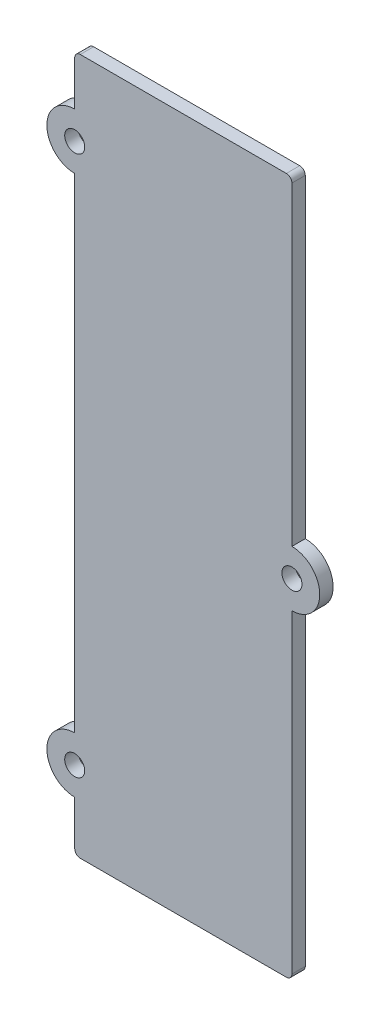
SolidWorks part; units mm, degrees
material "PET"
ref_plane "Front Plane" through (0, 0, 0) normal (0, 0, 1) x (1, 0, 0)
ref_plane "Top Plane" through (0, 0, 0) normal (0, 1, 0) x (1, 0, 0)
ref_plane "Right Plane" through (0, 0, 0) normal (1, 0, 0) x (0, 0, -1)
sketch "Sketch1" plane through (0, 0, 0) normal (0, 0, 1) x (1, 0, 0)
  line L1 (0, 0) -> (24.765, 0)
  line L2 (0, 0) -> (0, 79.375)
  line L3 (0, 79.375) -> (24.765, 79.375)
  line L4 (24.765, 0) -> (24.765, 79.375)
  dimension "D1" = 79.375
  dimension "D2" = 24.765
extrude "Boss-Extrude1" add sketch "Sketch1" along normal blind 1.524
sketch "Sketch2" plane through (0, 0, 1.524) normal (0, 0, 1) x (1, 0, 0)
  line L1 (24.765, 0) -> (24.765, 79.375) construction
  line L2 (0, 79.375) -> (0, 0) construction
  line L3 (0, 0) -> (24.765, 0) construction
  line L4 (24.765, 79.375) -> (0, 79.375) construction
  circle A0 centre (0, 8.89) radius 3.175
  circle A1 centre (24.765, 39.6875) radius 3.175
  circle A2 centre (0, 70.485) radius 3.175
  dimension "D1" = 6.35
  dimension "D2" = 6.35
  dimension "D3" = 6.35
  dimension "D4" = 8.89
  dimension "D5" = 8.89
extrude "Boss-Extrude2" add sketch "Sketch2" against normal up to surface (1.524 mm away) up to face at (12.3825, 39.6875, 0)
sketch "Sketch3" plane through (0, 0, 1.524) normal (0, 0, 1) x (1, 0, 0)
  line L0 (24.765, 36.5125) -> (24.765, 42.8625) construction
  line L1 (0, 5.715) -> (0, 12.065) construction
  line L2 (0, 67.31) -> (0, 73.66) construction
  circle A0 centre (0, 8.89) radius 1.143
  circle A1 centre (24.765, 39.6875) radius 1.143
  circle A2 centre (0, 70.485) radius 1.143
  dimension "D1" = 2.286
  dimension "D2" = 2.286
  dimension "D3" = 2.286
extrude "Cut-Extrude1" cut sketch "Sketch3" against normal through all
fillet "Fillet1" radius 0.635 4 edges at (0, 79.375, 0.762) (24.765, 79.375, 0.762) (24.765, 0, 0.762) (0, 0, 0.762)
